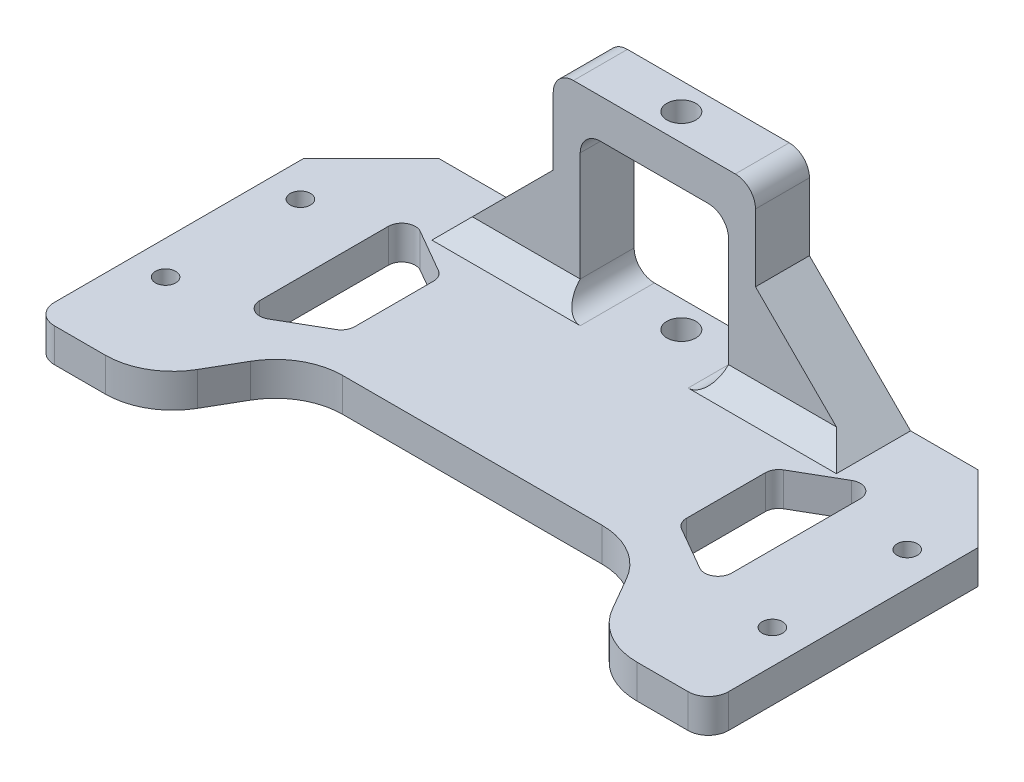
SolidWorks part; units mm, degrees
material "聚脂树脂"
ref_plane "前视基准面" through (0, 0, 0) normal (0, 0, 1) x (1, 0, 0)
ref_plane "上视基准面" through (0, 0, 0) normal (0, 1, 0) x (1, 0, 0)
ref_plane "右视基准面" through (0, 0, 0) normal (1, 0, 0) x (0, 0, -1)
other "Configuration Table"
sketch "草图1" plane through (0, 0, 0) normal (0, 1, 0) x (1, 0, 0)
  line L0 (-33.6603, -25) -> (-25, -10)
  line L1 (-50, -25) -> (50, -25)
  line L2 (-50, -25) -> (-50, 25)
  line L3 (-50, 25) -> (50, 25)
  line L4 (50, -25) -> (50, 25)
  line L5 (-50, -25) -> (50, 25) construction
  line L6 (-50, 25) -> (50, -25) construction
  line L7 (-25, -10) -> (25, -10)
  line L8 (25, -10) -> (33.6603, -25)
  point P0 (0, 0)
  dimension "D1" = 100
  dimension "D2" = 50
  dimension "D3" = 50
  dimension "D4" = 60
  dimension "D5" = 60
  dimension "D6" = 25
  dimension "D7" = 15
extrude "凸台-拉伸1" add sketch "草图1" along normal blind 5 contours L7 L8 L1 L4 L3 L2 L0
fillet "圆角1" radius 10 4 edges at (33.6603, 2.5, 25) (25, 2.5, 10) (-25, 2.5, 10) (-33.6603, 2.5, 25)
sketch "草图2" plane through (0, 0, -25) normal (0, 0, -1) x (-1, 0, 0)
  line L0 (-15, 5) -> (-15, 33)
  line L1 (50, 5) -> (-50, 5) construction
  line L2 (-15, 33) -> (15, 33)
  line L3 (0, 0) -> (0, 28.4022) construction
  line L4 (50, 0) -> (-50, 0) construction
  line L5 (-15, 5) -> (15, 5)
  line L6 (-11, 5) -> (-11, 27.2)
  line L7 (-11, 27.2) -> (11, 27.2)
  line L8 (11, 5) -> (11, 27.2)
  line L9 (15, 5) -> (15, 33)
  point P15 (0, 27.2)
  point P17 (0, 5)
  point P18 (0, 33)
  line M8 (50, 5) -> (-50, 5)
  dimension "D1" = 28
  dimension "D2" = 15
  dimension "D3" = 11
  dimension "D4" = 22.2
extrude "凸台-拉伸2" add sketch "草图2" against normal blind 8 contours L7 L3 L2 L0 L5 L6 | L3 L7 L8 L9 L2 M8
fillet "圆角4" radius 3 2 edges at (15, 33, -21) (-15, 33, -21)
sketch "草图3" plane through (0, 0, 0) normal (0, -1, 0) x (1, 0, 0)
  line L0 (0, 0) -> (0, 28.3867) construction
  line L1 (0, 0) -> (51.7948, 0) construction
  circle A0 centre (-45, 10.5) radius 1.5
  circle A1 centre (-45, -9.5) radius 1.5
  circle A2 centre (45, -9.5) radius 1.5
  circle A3 centre (45, 10.5) radius 1.5
  dimension "D1" = 3
  dimension "D2" = 3
  dimension "D6" = 45
  dimension "D3" = 20
  dimension "D4" = 45
  dimension "D5" = 10.5
extrude "切除-拉伸1" cut sketch "草图3" against normal blind 5
chamfer "倒角1" distance 10 angle 45 2 edges at (-50, 2.5, -25) (50, 2.5, -25)
fillet "圆角5" radius 3 2 edges at (-50, 2.5, 25) (50, 2.5, 25)
sketch "草图4" plane through (0, 5, 0) normal (0, 1, 0) x (1, 0, 0)
  line L0 (0, 0) -> (0, 28.8346) construction
  line L1 (0, 0) -> (-52.8392, 0) construction
  line L2 (-35, 16) -> (-35, -10)
  line L3 (-35, -10) -> (-24.6077, -4)
  line L4 (-24.6077, -4) -> (-24.6077, 10)
  line L5 (-24.6077, 10) -> (-35, 16)
  line L6 (24.6077, -4) -> (24.6077, 10)
  line L7 (35, -10) -> (24.6077, -4)
  line L8 (35, 16) -> (35, -10)
  line L9 (24.6077, 10) -> (35, 16)
  dimension "D1" = 26
  dimension "D2" = 14
  dimension "D3" = 60
  dimension "D4" = 60
  dimension "D5" = 35
  dimension "D6" = 16
extrude "切除-拉伸2" cut sketch "草图4" against normal blind 5
fillet "圆角6" radius 2 4 edges at (-35, 2.5, -16) (-24.6077, 2.5, -10) (-24.6077, 2.5, 4) (-35, 2.5, 10)
fillet "圆角7" radius 2 4 edges at (24.6077, 2.5, 4) (35, 2.5, 10) (35, 2.5, -16) (24.6077, 2.5, -10)
chamfer "倒角2" distance 15 angle 45 2 edges at (-15, 5, -21) (15, 5, -21)
fillet "圆角8" radius 3 4 edges at (-11, 27.2, -21) (11, 27.2, -21) (11, 5, -21) (-11, 5, -21)
sketch "草图6" plane through (0, 33, 0) normal (0, 1, 0) x (1, 0, 0)
  line L0 (0, 0) -> (0, 45.8785) construction
  line L1 (12, 25) -> (-12, 25) construction
  circle A0 centre (0, 21) radius 2.15
  dimension "D1" = 4.3
  dimension "D2" = 4
extrude "切除-拉伸3" cut sketch "草图6" against normal blind 52
chamfer "倒角3" distance 3 angle 45 2 edges at (19, 5, -17) (-19, 5, -17)
